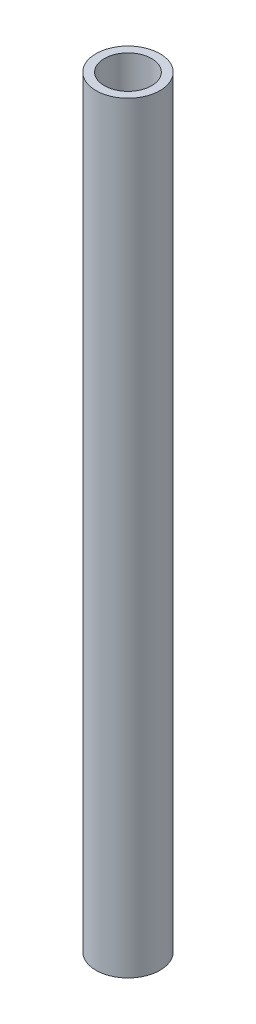
SolidWorks part; units mm, degrees
ref_plane "Front Plane" through (0, 0, 0) normal (0, 0, 1) x (1, 0, 0)
ref_plane "Top Plane" through (0, 0, 0) normal (0, 1, 0) x (1, 0, 0)
ref_plane "Right Plane" through (0, 0, 0) normal (1, 0, 0) x (0, 0, -1)
sketch "Sketch1" plane through (0, 0, 0) normal (0, 1, 0) x (1, 0, 0)
  circle A0 centre (0, 0) radius 7.874
  circle A1 centre (0, 0) radius 10.668
extrude "Boss-Extrude1" add sketch "Sketch1" along normal mid plane 254
